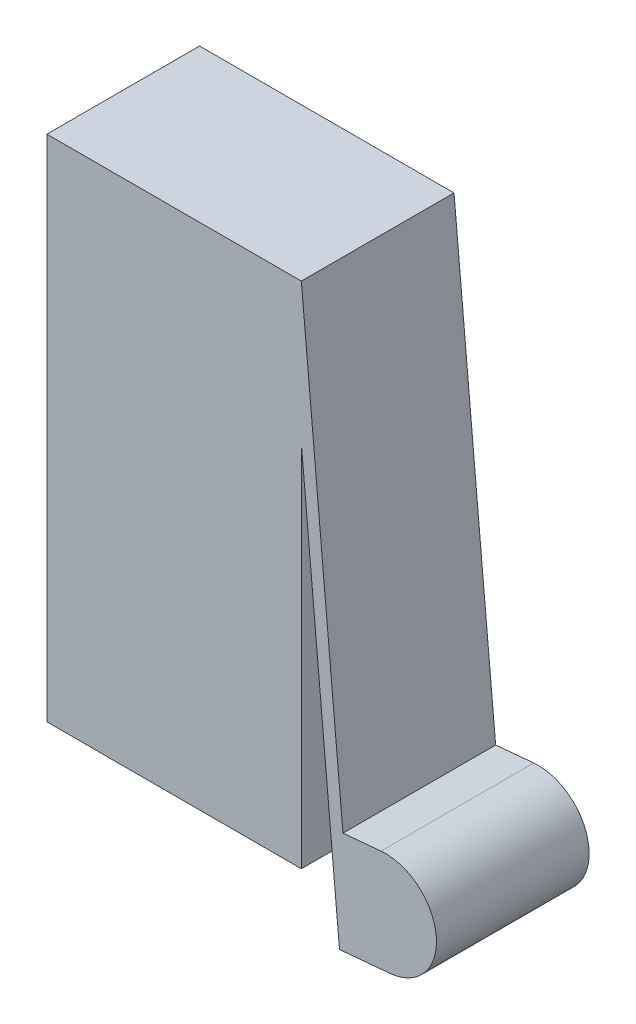
SolidWorks part; units mm, degrees
ref_plane "Płaszczyzna przednia" through (0, 0, 0) normal (0, 0, 1) x (1, 0, 0)
ref_plane "Płaszczyzna górna" through (0, 0, 0) normal (0, 1, 0) x (1, 0, 0)
ref_plane "Płaszczyzna prawa" through (0, 0, 0) normal (1, 0, 0) x (0, 0, -1)
sketch "Szkic1" plane through (0, 0, 0) normal (0, 0, 1) x (1, 0, 0)
  line L0 (10, 14.483) -> (11.5, -2)
  line L1 (0, 20) -> (10, 20)
  line L2 (0, 20) -> (0, 0)
  line L3 (0, 0) -> (10, 0)
  line L4 (10, 20) -> (10, 0)
  line L5 (10, 20) -> (11.6354, 2.0289)
  line L6 (11.5, -2) -> (13.4918, -1.8187)
  line L7 (11.6354, 2.0289) -> (13.1293, 2.1648)
  arc A0 (13.1293, 2.1648) -> (13.4918, -1.8187) centre (13.3105, 0.173) cw
  point P7 (12.3167, -0.7696)
  point P8 (0, 0)
  point P9 (0, 0)
  point P13 (0, 0)
  point P14 (0, 0)
  dimension "D4" = 2
  dimension "D1" = 10
  dimension "D2" = 20
  dimension "D3" = 0.5
  dimension "D5" = 2
  dimension "D6" = 1.5
  dimension "D7" = 2
extrude "Dodanie-wyciągnięcie1" add sketch "Szkic1" along normal blind 6 contours L4 L1 L2 L3 | A0 L7 L5 L4 L0 L6
